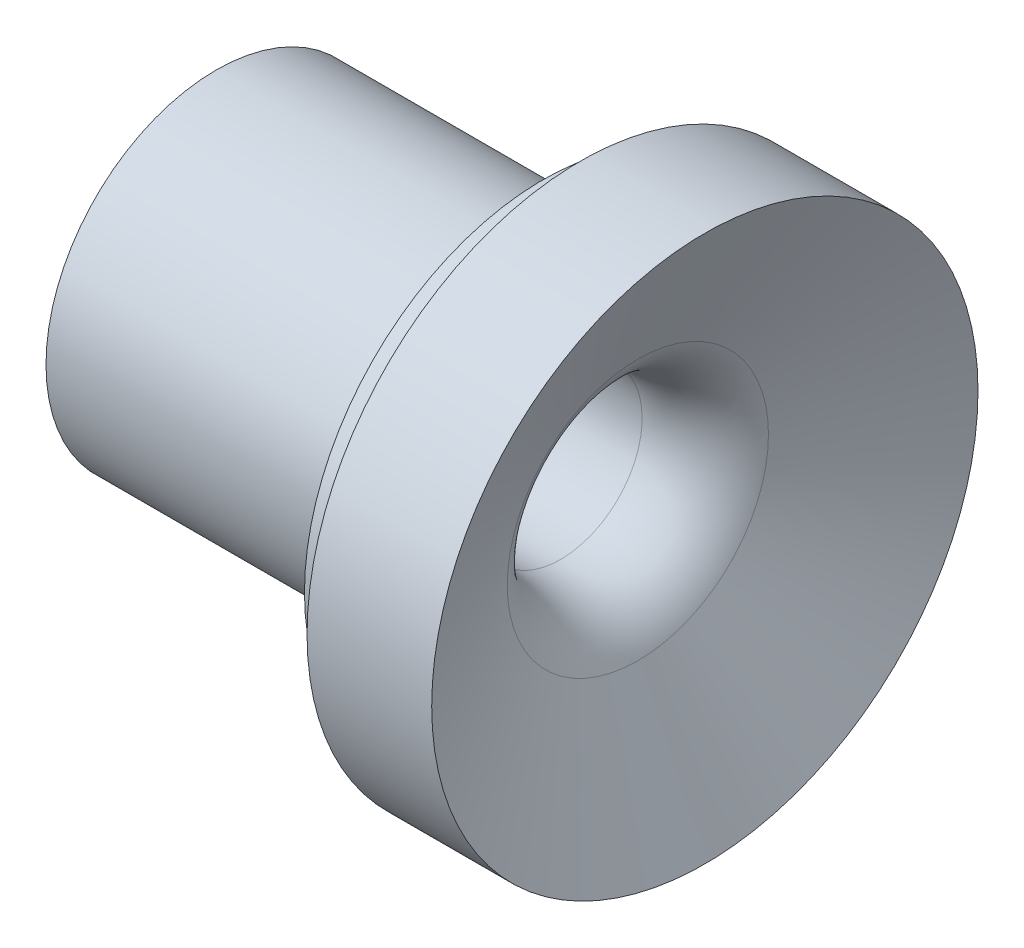
SolidWorks part; units mm, degrees
material "C (Graphite)"
ref_plane "Plan de face" through (0, 0, 0) normal (0, 0, 1) x (1, 0, 0)
ref_plane "Plan de dessus" through (0, 0, 0) normal (0, 1, 0) x (1, 0, 0)
ref_plane "Plan de droite" through (0, 0, 0) normal (1, 0, 0) x (0, 0, -1)
sketch "Esquisse1" plane through (0, 0, 0) normal (0, 0, 1) x (1, 0, 0)
  line L0 (1.9817, 8.978) -> (7.8235, 8.978)
  line L1 (7.8235, 8.978) -> (4.6838, 2.2984)
  line L3 (-5.0365, 0) -> (-15.0765, 1.816)
  line L4 (-15.0765, 1.816) -> (-15.0765, 4.152)
  line L5 (-15.0765, 4.152) -> (-2.0005, 4.152)
  line L6 (-1.3577, 4.3859) -> (-0.1282, 5.4177)
  line L7 (0.2291, 6.1837) -> (0.2291, 7.346)
  line L8 (0.2291, 7.346) -> (1.9817, 7.346)
  line L9 (1.9817, 7.346) -> (1.9817, 8.978)
  line L10 (-19.4769, -3.822) -> (13.1452, -3.822) construction
  line L11 (-5.0365, 0) -> (0.8035, 0)
  line L12 (0.8035, 0) -> (1.0638, 0)
  arc A0 (4.6838, 2.2984) -> (1.0638, 0) centre (1.0638, 4) cw
  arc A1 (-2.0005, 4.152) -> (-1.3577, 4.3859) centre (-2.0005, 5.152) ccw
  arc A2 (-0.1282, 5.4177) -> (0.2291, 6.1837) centre (-0.7709, 6.1837) ccw
  point P17 (3.6035, 0)
  point P20 (-1.6365, 4.152)
  point P23 (0.2291, 5.7174)
  dimension "D13" = 4
  dimension "D14" = 1
  dimension "D1" = 5.8418
  dimension "D2" = 7.974
  dimension "D3" = 13.44
  dimension "D4" = 7.5944
  dimension "D5" = 11.168
  dimension "D6" = 2.336
  dimension "D7" = 22.9
  dimension "D8" = 10.04
  dimension "D9" = 5.84
  dimension "D11" = 12.8
  dimension "D12" = 2.8
revolve "Révolution1" add sketch "Esquisse1" angle 360 about L10
